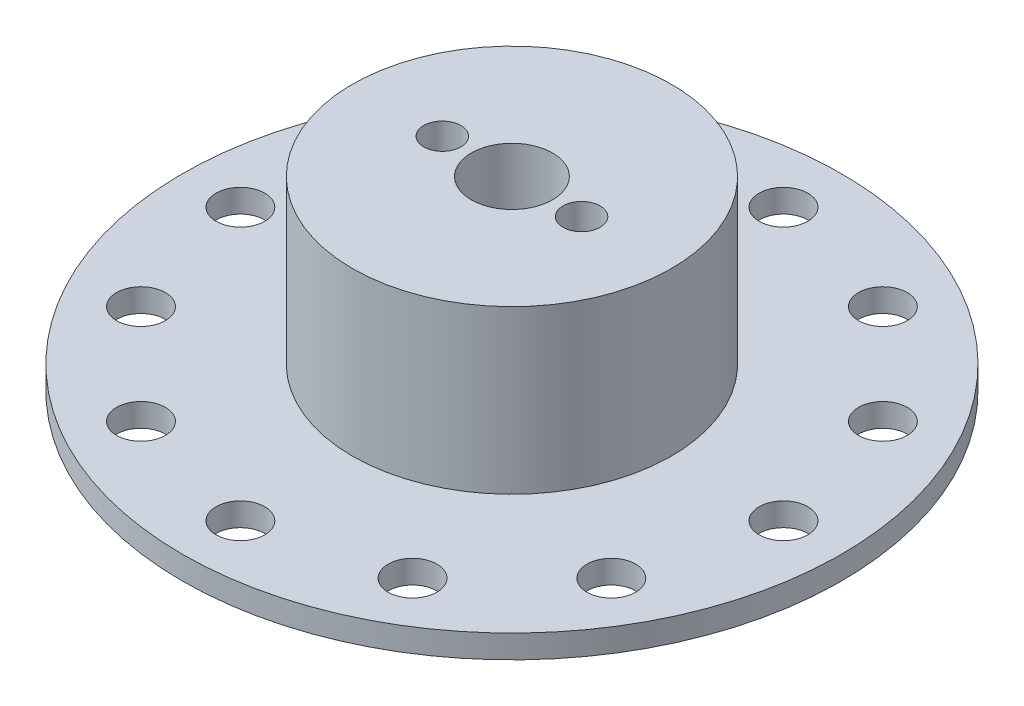
SolidWorks part; units mm, degrees
ref_plane "正面" through (0, 0, 0) normal (0, 0, 1) x (1, 0, 0)
ref_plane "平面" through (0, 0, 0) normal (0, 1, 0) x (1, 0, 0)
ref_plane "右側面" through (0, 0, 0) normal (1, 0, 0) x (0, 0, -1)
sketch "ｽｹｯﾁ1" plane through (0, 0, 0) normal (0, 1, 0) x (1, 0, 0)
  circle A0 centre (0, 0) radius 28.4
  dimension "D1" = 56.8
extrude "ﾎﾞｽ - 押し出し1" add sketch "ｽｹｯﾁ1" along normal blind 2
sketch "ｽｹｯﾁ2" plane through (0, 2, 0) normal (0, 1, 0) x (1, 0, 0)
  circle A0 centre (0, 0) radius 13.75
  dimension "D1" = 27.5
extrude "ﾎﾞｽ - 押し出し2" add sketch "ｽｹｯﾁ2" along normal blind 14
sketch "ｽｹｯﾁ3" plane through (0, 16, 0) normal (0, 1, 0) x (1, 0, 0)
  line L0 (-6, 0) -> (6, 0) construction
  circle A0 centre (0, 0) radius 3.5
  circle A1 centre (-6, 0) radius 1.6
  circle A2 centre (6, 0) radius 1.6
  point P6 (0, 0)
  dimension "D1" = 7
  dimension "D2" = 3.2
  dimension "D3" = 12
extrude "ｶｯﾄ - 押し出し1" cut sketch "ｽｹｯﾁ3" against normal through all
sketch "ｽｹｯﾁ4" plane through (0, 2, 0) normal (0, 1, 0) x (1, 0, 0)
  line L0 (0, -23.4) -> (0, 23.4) construction
  line L1 (0, 23.4) -> (0, 28.4) construction
  line L2 (0, -23.4) -> (0, -28.4) construction
  circle A1 centre (11.7, 20.265) radius 2.1
  circle A2 centre (0, 0) radius 28.4 construction
  circle A3 centre (0, 23.4) radius 2.1
  circle A4 centre (0, -23.4) radius 2.1
  circle A5 centre (20.265, 11.7) radius 2.1
  circle A6 centre (23.4, 0) radius 2.1
  circle A7 centre (20.265, -11.7) radius 2.1
  circle A8 centre (11.7, -20.265) radius 2.1
  circle A9 centre (0, -23.4) radius 2.1
  circle A10 centre (-11.7, -20.265) radius 2.1
  circle A11 centre (-20.265, -11.7) radius 2.1
  circle A12 centre (-23.4, 0) radius 2.1
  circle A13 centre (-20.265, 11.7) radius 2.1
  circle A14 centre (-11.7, 20.265) radius 2.1
  point P4 (0, 0)
  point P35 (0, 0)
  dimension "D1" = 5
  dimension "D2" = 4.2
  dimension "D3" = 12
extrude "ｶｯﾄ - 押し出し2" cut sketch "ｽｹｯﾁ4" against normal through all contours A3 | A1 | A5 | A6 | A7 | A8 | A4 | A10 | A11 | A12 | A13 | A14
